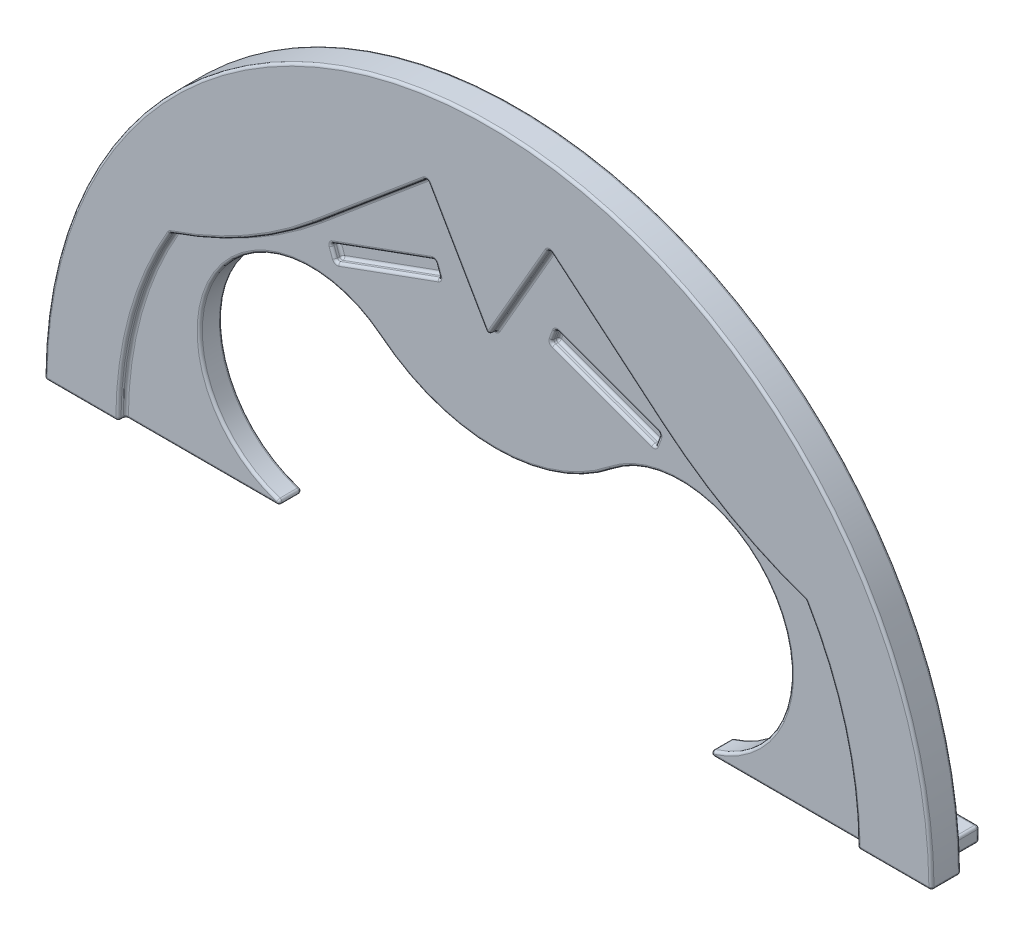
SolidWorks part; units mm, degrees
ref_plane "前视基准面" through (0, 0, 0) normal (0, 0, 1) x (1, 0, 0)
ref_plane "上视基准面" through (0, 0, 0) normal (0, 1, 0) x (1, 0, 0)
ref_plane "右视基准面" through (0, 0, 0) normal (1, 0, 0) x (0, 0, -1)
other "Configuration Table"
sketch "草图1" plane through (0, 0, 0) normal (0, 0, 1) x (1, 0, 0)
  line L0 (-120, 0) -> (120, 0)
  line L1 (55, 0) -> (-55, 0) construction
  arc A0 (120, 0) -> (-120, 0) centre (0, 0) ccw
  dimension "D2" = 240
extrude "凸台-拉伸1" add sketch "草图1" along normal blind 6
sketch "草图2" plane through (0, 0, 0) normal (0, 0, -1) x (-1, 0, 0)
  line L0 (3.3, 0) -> (-3.3, 0) construction
  line L1 (-115, 0) -> (-95, 0)
  line L2 (-115, 0) -> (-115, 4)
  line L3 (-115, 4) -> (-95, 4)
  line L4 (-95, 0) -> (-95, 4)
  line L6 (0, 3.3) -> (0, -3.3) construction
  dimension "D1" = 20
  dimension "D2" = 4
  dimension "D3" = 95
extrude "凸台-拉伸2" add sketch "草图2" along normal blind 10
mirror "镜向1" about plane through (0, 0, 0) normal (1, 0, 0) of "凸台-拉伸2"
hole_wizard "M2 六角头机械螺钉的柱形沉头孔1" positions "草图5" profile "草图4" counterbore size "M2" standard "ANSI Metric" end condition up to next
sketch "草图5" plane through (0, 4, 0) normal (0, 1, 0) x (1, 0, 0)
  line L0 (-66, 0) -> (66, 0) construction
  line L1 (-115, 10) -> (-115, 0) construction
  line L2 (115, 10) -> (115, 0) construction
  line L3 (95, 10) -> (95, 0) construction
  line L4 (-95, 10) -> (-95, 0) construction
  point P0 (-110, 5)
  point P2 (110, 5)
  point P10 (100, 5)
  point P15 (-100, 5)
  dimension "D1" = 5
  dimension "D2" = 5
  dimension "D3" = 5
  dimension "D4" = 5
  dimension "D5" = 5
  dimension "D6" = 5
  dimension "D7" = 5
  dimension "D8" = 5
sketch "草图4" plane through (-110, 4, -5) normal (1, 0, 0) x (0, 0, 1)
  line L0 (0, 0) -> (0, 4)
  line L1 (0, 4) -> (1.1, 4)
  line L3 (1.1, 4) -> (1.1, 2)
  line L4 (1.1, 2) -> (2.3, 2)
  line L5 (2.3, 2) -> (2.3, 0)
  line L7 (2.3, 0) -> (0, 0)
  line L11 (0, -6.35) -> (0, 107.95) construction
  dimension "通孔孔直径" = 2.2
  dimension "通孔孔深度" = 4
  dimension "柱形沉头孔直径" = 4.6
  dimension "柱形沉头孔深度" = 2
sketch "草图6" plane through (0, 0, 6) normal (0, 0, 1) x (1, 0, 0)
  line L0 (8.8, 0) -> (-8.8, 0) construction
  line L1 (0, -8.8) -> (0, 8.8) construction
  line L2 (-50, 0) -> (50, 0)
  arc A0 (50, 0) -> (31.25, 53.4187) centre (50, 30) ccw
  arc A1 (-50, 0) -> (-31.25, 53.4187) centre (-50, 30) cw
  arc A3 (-31.25, 53.4187) -> (31.25, 53.4187) centre (0, 92.45) ccw
  point P5 (50, 30)
  dimension "D1" = 60
  dimension "D5" = 0
  dimension "D4" = 50
  dimension "D2" = 30
  dimension "D3" = 50
extrude "切除-拉伸1" cut sketch "草图6" against normal up to next
sketch "草图8" plane through (0, 0, 6) normal (0, 0, 1) x (1, 0, 0)
  line L0 (-16.3681, 78.7588) -> (-44.5589, 68.4982)
  line L1 (-44.5589, 68.4982) -> (-43.1908, 64.7394)
  line L2 (-43.1908, 64.7394) -> (-15, 75)
  line L3 (-15, 75) -> (-16.3681, 78.7588)
  line L4 (0, -8.8) -> (0, 8.8) construction
  line L5 (8.8, 0) -> (-8.8, 0) construction
  line L6 (43.1908, 64.7394) -> (15, 75)
  line L7 (44.5589, 68.4982) -> (43.1908, 64.7394)
  line L8 (16.3681, 78.7588) -> (44.5589, 68.4982)
  line L9 (15, 75) -> (16.3681, 78.7588)
  dimension "D1" = 30
  dimension "D2" = 4
  dimension "D3" = 20
  dimension "D4" = 15
  dimension "D5" = 75
extrude "切除-拉伸2" cut sketch "草图8" against normal blind 2
sketch "草图10" plane through (0, 0, 6) normal (0, 0, 1) x (1, 0, 0)
  line L1 (8.8, 0) -> (-8.8, 0) construction
  line L3 (50, 0) -> (120, 0) construction
  line L5 (-120, 0) -> (-100, 0)
  line L9 (-16.5266, 98.6249) -> (-47.1684, 72.9134)
  line L10 (100, 0) -> (120, 0)
  line L11 (0, -8.8) -> (0, 8.8) construction
  line L12 (0, 70) -> (-16.5266, 98.6249)
  line L13 (0, 70) -> (16.5266, 98.6249)
  line L15 (16.5266, 98.6249) -> (47.1684, 72.9134)
  arc A1 (120, 0) -> (-120, 0) centre (0, 0) ccw construction
  arc A6 (100, 0) -> (85.9357, 51.1375) centre (0, 0) ccw
  arc A7 (120, 0) -> (-120, 0) centre (0, 0) ccw
  arc A9 (-85.9357, 51.1375) -> (-47.1684, 72.9134) centre (-124.3029, 164.8387) ccw
  arc A10 (-85.9357, 51.1375) -> (-100, 0) centre (0, 0) ccw
  arc A11 (47.1684, 72.9134) -> (85.9357, 51.1375) centre (124.3029, 164.8387) ccw
  point P1 (0, 70)
  dimension "D1" = 100
  dimension "D11" = 34.0643
  dimension "D12" = 120
  dimension "D13" = 34.0643
  dimension "D9" = 100
  dimension "D3" = 30
  dimension "D4" = 30
  dimension "D5" = 40
  dimension "D6" = 40
  dimension "D7" = 80
  dimension "D8" = 47.1684
  dimension "D10" = 120
extrude "凸台-拉伸3" add sketch "草图10" along normal blind 2
fillet "圆角1" radius 0.7 89 edges at (95, 0, -5) (95, 2, 0) (75, 0, 6) (-115, 2, 0) (-115, 4, -5) (-115, 0, -5) (-115, 2, -10) (-105, 4, 0) (-95, 0, -5) (-95, 4, -5) (-105, 4, -10) (-105, 0, -10) (-95, 2, -10) (-95, 2, 0) (95, 4, -5) (95, 2, -10) (105, 0, -10) (117.5, 0, 0) (115, 2, 0) (115, 0, -5) (105, 4, 0) (115, 4, -5) (105, 4, -10) (-72.5, 0, 0) (-50, 0, 3) (50, 0, 3) (-78.3069, 39.9357, 0) (0, 42.45, 0) (78.3069, 39.9357, 0) (78.3069, 39.9357, 6) (72.5, 0, 0) (-120, 0, 4) (120, 0, 4) (110, 0, 8) (-110, 0, 8) (0, 42.45, 6) (-78.3069, 39.9357, 6) (-75, 0, 6) (-117.5, 0, 0) (0, 120, 0) (43.8748, 66.6188, 6) (44.5589, 68.4982, 5) (30.4635, 73.6285, 4) (16.3681, 78.7588, 5) (15.684, 76.8794, 4) (15, 75, 5) (29.0954, 69.8697, 6) (29.0954, 69.8697, 4) (43.1908, 64.7394, 5) (43.8748, 66.6188, 4) (15.684, 76.8794, 6) (30.4635, 73.6285, 6) (-15, 75, 5) (-16.3681, 78.7588, 5) (-30.4635, 73.6285, 6) (-43.1908, 64.7394, 5) (-29.0954, 69.8697, 4) (-43.8748, 66.6188, 4) (-44.5589, 68.4982, 5) (-43.8748, 66.6188, 6) (-30.4635, 73.6285, 4) (-29.0954, 69.8697, 6) (-15.684, 76.8794, 4) (-15.684, 76.8794, 6) (100, 0, 7) (-100, 0, 7) (0, 70, 7) (-8.2633, 84.3125, 6) (-31.8475, 85.7692, 6) (16.5266, 98.6249, 7) (8.2633, 84.3125, 8) (0, 120, 8) (-85.9357, 51.1375, 7) (96.4198, 26.5182, 6) (85.9357, 51.1375, 7) (96.4198, 26.5182, 8) (65.5347, 60.2142, 8) (65.5347, 60.2142, 6) (-96.4198, 26.5182, 6) (-96.4198, 26.5182, 8) (-16.5266, 98.6249, 7) (31.8475, 85.7692, 6) (31.8475, 85.7692, 8) (8.2633, 84.3125, 6) (-8.2633, 84.3125, 8) (-31.8475, 85.7692, 8) (-65.5347, 60.2142, 6) (-65.5347, 60.2142, 8) (115, 2, -10)
fillet "圆角2" radius 0.3 4 edges at (-110, 4, -2.7) (-100, 4, -2.7) (100, 4, -2.7) (110, 4, -2.7)
